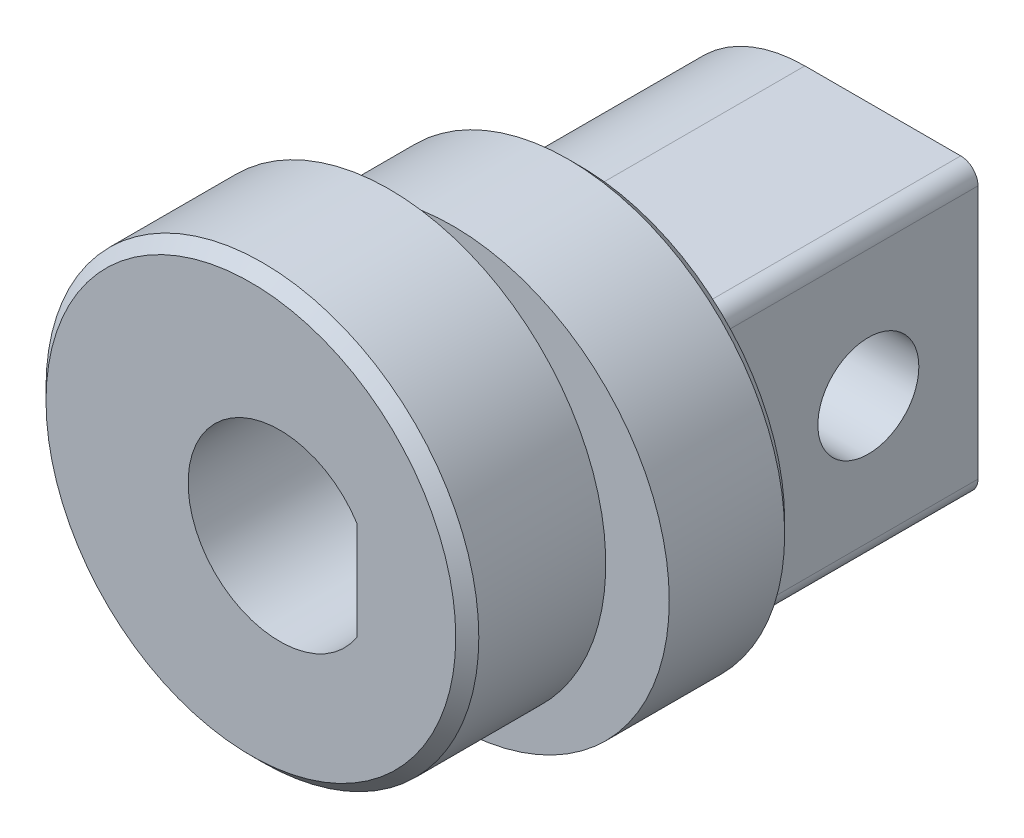
SolidWorks part; units mm, degrees
ref_plane "Ebene vorne" through (0, 0, 0) normal (0, 0, 1) x (1, 0, 0)
ref_plane "Ebene oben" through (0, 0, 0) normal (0, 1, 0) x (1, 0, 0)
ref_plane "Ebene rechts" through (0, 0, 0) normal (1, 0, 0) x (0, 0, -1)
ref_plane "Plane2" through (0, 0, 0.4) normal (0, 0, 1) x (1, 0, 0)
sketch "Sketch10" plane through (0, 0, 0.4) normal (0, 0, 1) x (1, 0, 0)
  circle A0 centre (1.2, 0) radius 7.5
  dimension "D1" = 15
extrude "Boss-Extrude4" add sketch "Sketch10" along normal blind 4.2 and the other way blind 0.2
sketch "Sketch11" plane through (0, 0, 0.2) normal (0, 0, -1) x (-1, 0, 0)
  line L0 (-6, -4.4) -> (-6, 4.4)
  line L1 (-5.4, 5) -> (0, 5)
  line L2 (0, -5) -> (-5.4, -5)
  arc A2 (0, 5) -> (0, -5) centre (0, 0) cw
  arc A3 (-6, 4.4) -> (-5.4, 5) centre (-5.4, 4.4) cw
  arc A4 (-5.4, -5) -> (-6, -4.4) centre (-5.4, -4.4) cw
  dimension "D1" = 5
  dimension "D3" = 0.6
  dimension "D2" = 6
extrude "Boss-Extrude5" add sketch "Sketch11" along normal blind 9
ref_plane "Plane3" through (0, 0, 4.6) normal (0, 0, -1) x (-1, 0, 0)
sketch "Sketch16" plane through (0, 0, 4.6) normal (0, 0, -1) x (-1, 0, 0)
  circle A0 centre (1, 0) radius 7.5
  dimension "D1" = 15
  dimension "D2" = 1
extrude "Boss-Extrude6" add sketch "Sketch16" against normal blind 4.8
sketch "Sketch17" plane through (0, 0, 9.4) normal (0, 0, 1) x (1, 0, 0)
  line L0 (2.675, -1.7103) -> (2.675, 1.7103)
  line L1 (-3.175, 0) -> (-3.175, 1.4955) construction
  arc A0 (2.675, 1.7103) -> (2.675, -1.7103) centre (0, 0) ccw
  dimension "D1" = 3.175
  dimension "D2" = 5.85
extrude "Cut-Extrude2" cut sketch "Sketch17" against normal through all
hole_wizard "Ø3.5 (3.5) Diameter Hole0" positions "Sketch19" profile "Sketch18" hole size "Ø3.5" standard "ANSI Metric"
sketch "Sketch19" plane through (6, 0, 0) normal (1, 0, 0) x (0, 0, -1)
  point P0 (5, 0)
sketch "Sketch18" plane through (6, 0, -5) normal (0, 1, 0) x (0, 0, -1)
  line L0 (0, 0) -> (0, 5.0515)
  line L1 (0, 5.0515) -> (1.75, 4)
  line L2 (1.75, 4) -> (1.75, 0)
  line L5 (1.75, 0) -> (0, 0)
  line L10 (0, 5.0515) -> (-1.75, 4) construction
  line L11 (0, -6.35) -> (0, 107.95) construction
  dimension "Hole Dia." = 3.5
  dimension "Hole Depth" = 4
  dimension "Drill Angle" = 118
chamfer "Chamfer2" distance 0.4 angle 45 2 edges at (-8.5, 0, 9.4) (8.7, 0, 0.2)
